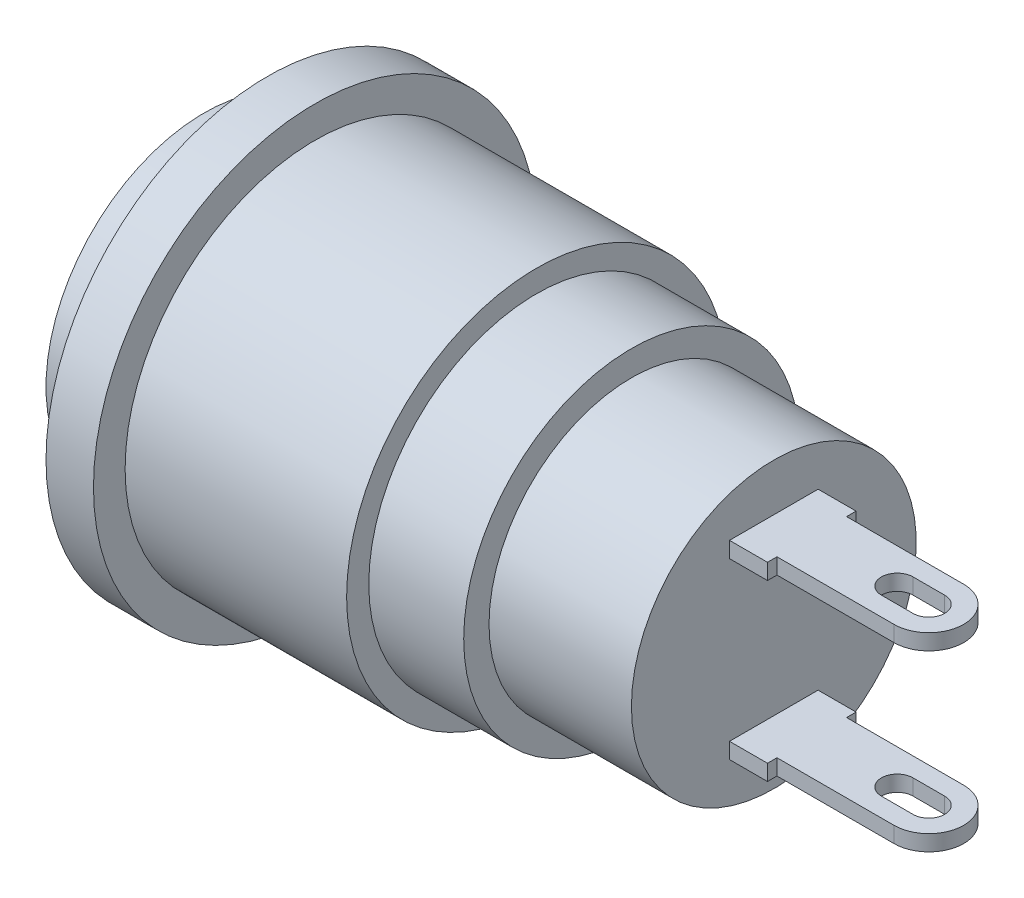
SolidWorks part; units mm, degrees
ref_plane "Front Plane" through (0, 0, 0) normal (0, 0, 1) x (1, 0, 0)
ref_plane "Top Plane" through (0, 0, 0) normal (0, 1, 0) x (1, 0, 0)
ref_plane "Right Plane" through (0, 0, 0) normal (1, 0, 0) x (0, 0, -1)
sketch "Sketch1" plane through (0, 0, 0) normal (0, 1, 0) x (1, 0, 0)
  line L0 (-8, 0) -> (8, 0)
  line L1 (-6.5, 6) -> (0.5, 6)
  line L2 (0.5, 6) -> (0.5, 5.3)
  line L3 (0.5, 5.3) -> (3.5, 5.3)
  line L4 (3.5, 5.3) -> (3.5, 4.5)
  line L5 (3.5, 4.5) -> (8, 4.5)
  line L6 (8, 4.5) -> (8, 0)
  line L7 (-6.5, 6) -> (-6.5, 7)
  line L8 (-6.5, 7) -> (-8, 7)
  line L9 (-8, 7) -> (-8, 0)
  point P0 (-7.9307, 5)
  dimension "D2" = 1.5
  dimension "D4" = 6
  dimension "D5" = 7
  dimension "D6" = 4.5
  dimension "D7" = 4.5
  dimension "D8" = 5.3
  dimension "D9" = 3
  dimension "D10" = 16
revolve "Revolve1" add sketch "Sketch1" angle 360 about L0
sketch "Sketch2" plane through (0, 0, 0) normal (0, 1, 0) x (1, 0, 0)
  line L0 (-8, 0) -> (-11, 0)
  line L1 (-8, 7) -> (-8, -7) construction
  line L3 (-8, 0) -> (-8, 5)
  line L4 (-8, 5) -> (-10, 5)
  spline S0 degree 2 poles (-11, 0) (-11, 2.6515) (-10, 5) knots 0 0 0 1 1 1
  dimension "D1" = 3
  dimension "D2" = 2
  dimension "D3" = 5
revolve "Revolve2" add sketch "Sketch2" angle 360 about L0
ref_plane "Plane1" through (0, 3, 0) normal (0, 1, 0) x (1, 0, 0)
sketch "Sketch3" plane through (0, 3, 0) normal (0, 1, 0) x (1, 0, 0)
  line L0 (0, 0) -> (12.9, 0) construction
  line L1 (8, -1.4) -> (8, 1.4)
  line L2 (8, 1.4) -> (9.2, 1.4)
  line L3 (9.2, 1.4) -> (9.2, 1.1)
  line L4 (9.2, 1.1) -> (12.9, 1.1)
  line L5 (9.2, -1.1) -> (12.9, -1.1)
  line L6 (9.2, -1.4) -> (9.2, -1.1)
  line L7 (8, -1.4) -> (9.2, -1.4)
  line L8 (12.9, 0) -> (14, 0) construction
  line L9 (8, -4.5) -> (8, 4.5) construction
  line L10 (11.9, 0) -> (12.9, 0) construction
  line L11 (11.9, 0.5) -> (12.9, 0.5)
  line L12 (11.9, -0.5) -> (12.9, -0.5)
  arc A0 (12.9, 1.1) -> (12.9, -1.1) centre (12.9, 0) cw
  arc A1 (11.9, 0.5) -> (11.9, -0.5) centre (11.9, 0) ccw
  arc A2 (12.9, -0.5) -> (12.9, 0.5) centre (12.9, 0) ccw
  point P3 (12.4, 0)
  point P12 (8, 0)
  dimension "D7" = 1.6
  dimension "D1" = 2.8
  dimension "D2" = 2.2
  dimension "D3" = 1.2
  dimension "D4" = 6
  dimension "D5" = 1
  dimension "D6" = 1
extrude "Boss-Extrude1" add sketch "Sketch3" against normal blind 0.5
mirror "Mirror1" about plane through (0, 0, 0) normal (0, 1, 0) of "Boss-Extrude1"
